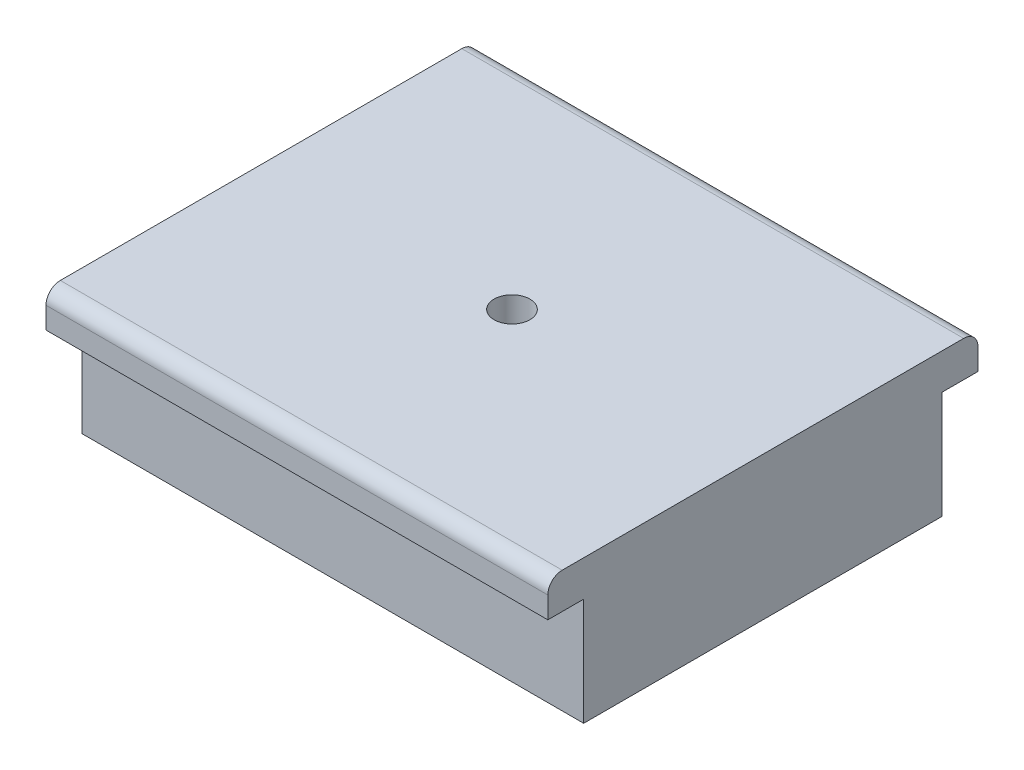
SolidWorks part; units mm, degrees
ref_plane "Front Plane" through (0, 0, 0) normal (0, 0, 1) x (1, 0, 0)
ref_plane "Top Plane" through (0, 0, 0) normal (0, 1, 0) x (1, 0, 0)
ref_plane "Right Plane" through (0, 0, 0) normal (1, 0, 0) x (0, 0, -1)
sketch "Sketch1" plane through (0, 0, 0) normal (0, 1, 0) x (1, 0, 0)
  line L1 (35, 25) -> (-35, 25)
  line L2 (35, 25) -> (35, -25)
  line L3 (35, -25) -> (-35, -25)
  line L4 (-35, 25) -> (-35, -25)
  point P0 (0, 0)
  dimension "D1" = 50
  dimension "D2" = 70
extrude "Boss-Extrude1" add sketch "Sketch1" along normal blind 7.5 and the other way blind 7.5
sketch "Sketch2" plane through (0, 7.5, 0) normal (0, 1, 0) x (1, 0, 0)
  line L1 (-35, -30) -> (35, -30)
  line L2 (-35, -30) -> (-35, 30)
  line L3 (-35, 30) -> (35, 30)
  line L4 (35, -30) -> (35, 30)
  line L5 (-35, -30) -> (35, 30) construction
  line L6 (-35, 30) -> (35, -30) construction
  point P0 (0, 0)
extrude "Boss-Extrude2" add sketch "Sketch2" along normal blind 5
fillet "Fillet1" radius 2 2 edges at (0, 12.5, -30) (0, 12.5, 30)
sketch "Sketch3" plane through (0, 12.5, 0) normal (0, 1, 0) x (1, 0, 0)
  circle A0 centre (0, 0) radius 2.5
extrude "Cut-Extrude1" cut sketch "Sketch3" against normal blind 10
